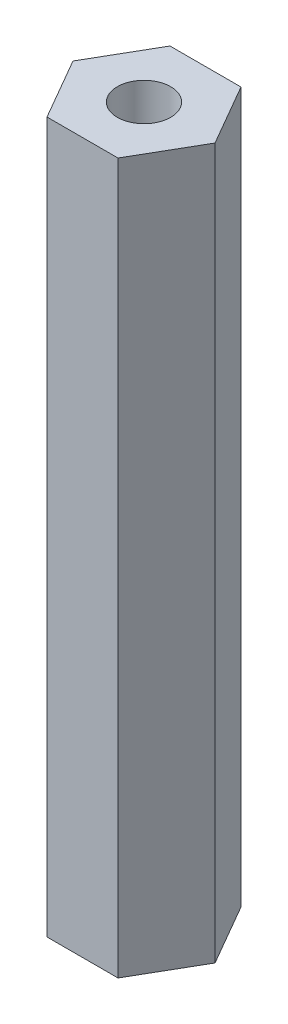
SolidWorks part; units mm, degrees
material "Brass"
ref_plane "Front Plane" through (0, 0, 0) normal (0, 0, 1) x (1, 0, 0)
ref_plane "Top Plane" through (0, 0, 0) normal (0, 1, 0) x (1, 0, 0)
ref_plane "Right Plane" through (0, 0, 0) normal (1, 0, 0) x (0, 0, -1)
sketch "Sketch1" plane through (0, 0, 0) normal (0, 1, 0) x (1, 0, 0)
  line L1 (-4, 0) -> (-2, -3.4641)
  line L2 (-2, -3.4641) -> (2, -3.4641)
  line L3 (2, -3.4641) -> (4, 0)
  line L4 (4, 0) -> (2, 3.4641)
  line L5 (2, 3.4641) -> (-2, 3.4641)
  line L6 (-2, 3.4641) -> (-4, 0)
  circle A0 centre (0, 0) radius 3.4641 construction
  dimension "D1" = 4
  dimension "D2" = 4
extrude "Boss-Extrude1" add sketch "Sketch1" along normal blind 40
sketch "Sketch2" plane through (0, 40, 0) normal (0, 1, 0) x (1, 0, 0)
  circle A0 centre (0, 0) radius 1.5
  dimension "D1" = 3
extrude "Cut-Extrude1" cut sketch "Sketch2" against normal blind 40
